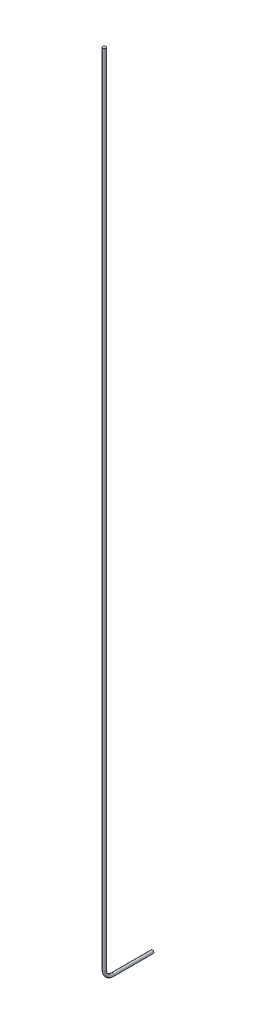
SolidWorks part; units mm, degrees
ref_plane "正面" through (0, 0, 0) normal (0, 0, 1) x (1, 0, 0)
ref_plane "平面" through (0, 0, 0) normal (0, 1, 0) x (1, 0, 0)
ref_plane "右側面" through (0, 0, 0) normal (1, 0, 0) x (0, 0, -1)
sketch "ｽｹｯﾁ1" plane through (0, 0, 0) normal (0, 0, 1) x (1, 0, 0)
  circle A0 centre (0, 0) radius 0.98
  dimension "D1" = 1.96
extrude "ﾎﾞｽ - 押し出し1" add sketch "ｽｹｯﾁ1" along normal blind 20
sketch "ｽｹｯﾁ2" plane through (0, 0, 20) normal (0, 0, 1) x (1, 0, 0)
  circle A1 centre (0, 0) radius 0.98
  circle A2 centre (0, 0) radius 0.98
  dimension "D1" = 0
sketch "ｽｹｯﾁ3" plane through (0, 0, 0) normal (1, 0, 0) x (0, 0, -1)
  line L0 (-20, 0) -> (-25, 0)
  line L1 (-20, 0.98) -> (-20, -0.98) construction
  line L2 (-30, 5) -> (-30, 505)
  line L3 (-20, 0.98) -> (-20, -0.98) construction
  arc A0 (-25, 0) -> (-30, 5) centre (-25, 5) cw
  point P8 (-30, 0)
  dimension "D2" = 5
  dimension "D1" = 10
  dimension "D3" = 500
sweep "ｽｲｰﾌﾟ1" add profiles "ｽｹｯﾁ2" path "ｽｹｯﾁ3"
